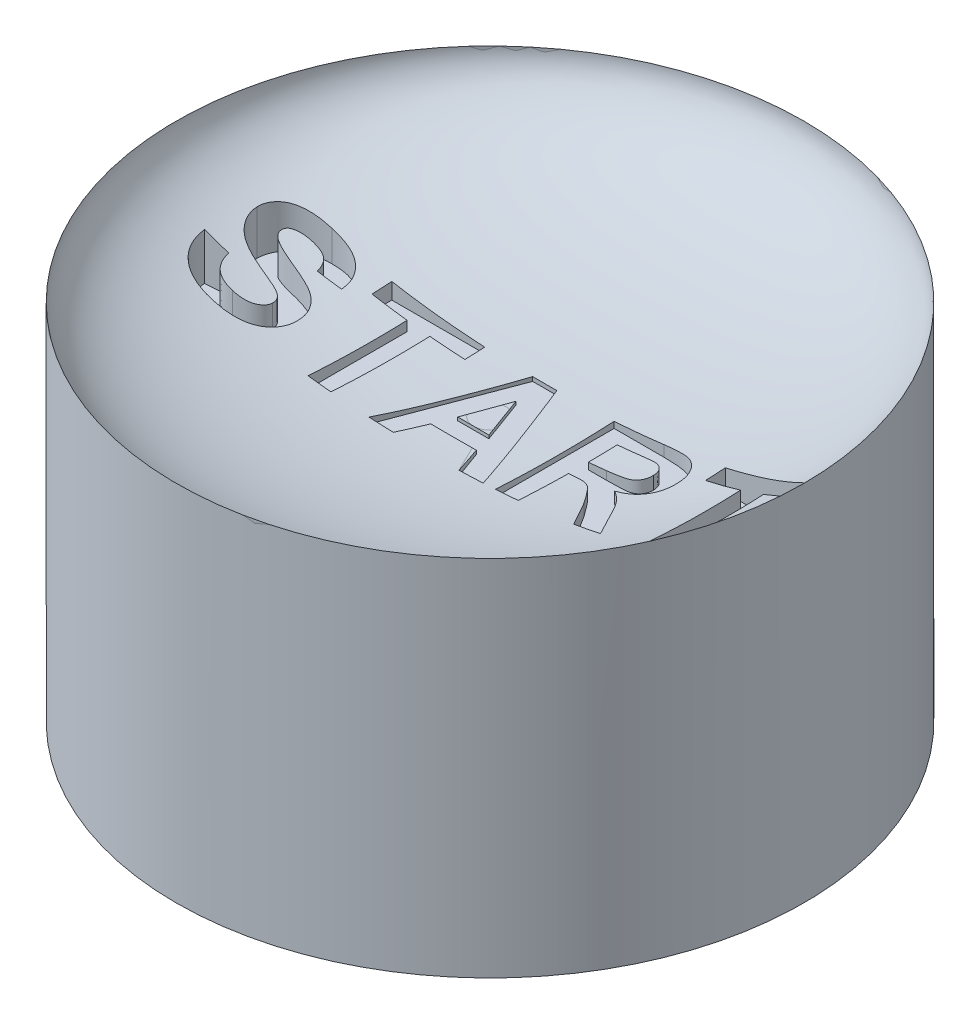
SolidWorks part; units mm, degrees
material "ABS"
ref_plane "Front Plane" through (0, 0, 0) normal (0, 0, 1) x (1, 0, 0)
ref_plane "Top Plane" through (0, 0, 0) normal (0, 1, 0) x (1, 0, 0)
ref_plane "Right Plane" through (0, 0, 0) normal (1, 0, 0) x (0, 0, -1)
sketch "Sketch1" plane through (0, 0, 0) normal (0, 1, 0) x (1, 0, 0)
  circle A0 centre (0, 0) radius 9.5
  dimension "D1" = 19
extrude "Boss-Extrude1" add sketch "Sketch1" along normal blind 8
sketch "Sketch6" plane through (0, 0, 0) normal (1, 0, 0) x (0, 0, -1)
  line L0 (0, 8) -> (0, 11.4053) construction
  line L1 (9.5, 8) -> (-9.5, 8) construction
  line L2 (-9.5, 8) -> (-9.5, 11)
  line L3 (-9.5, 8) -> (-0.5, 8)
  ellipse E0 centre (-0.5, 11) end of major axis (8.5, 11) minor radius 3 (-9.5, 11) -> (-0.5, 8) ccw
  dimension "D1" = 3
  dimension "D2" = 9
revolve "Revolve4" add sketch "Sketch6" angle 360 about L0
ref_plane "Plane1" through (0, 10, 0) normal (0, 1, 0) x (1, 0, 0)
sketch "Sketch7" plane through (0, 10, 0) normal (0, 1, 0) x (1, 0, 0)
  text T0 "START" font "Arial" height in points 14
  point P0 (0, 0)
extrude "Cut-Extrude1" cut sketch "Sketch7" against normal blind 2.1
